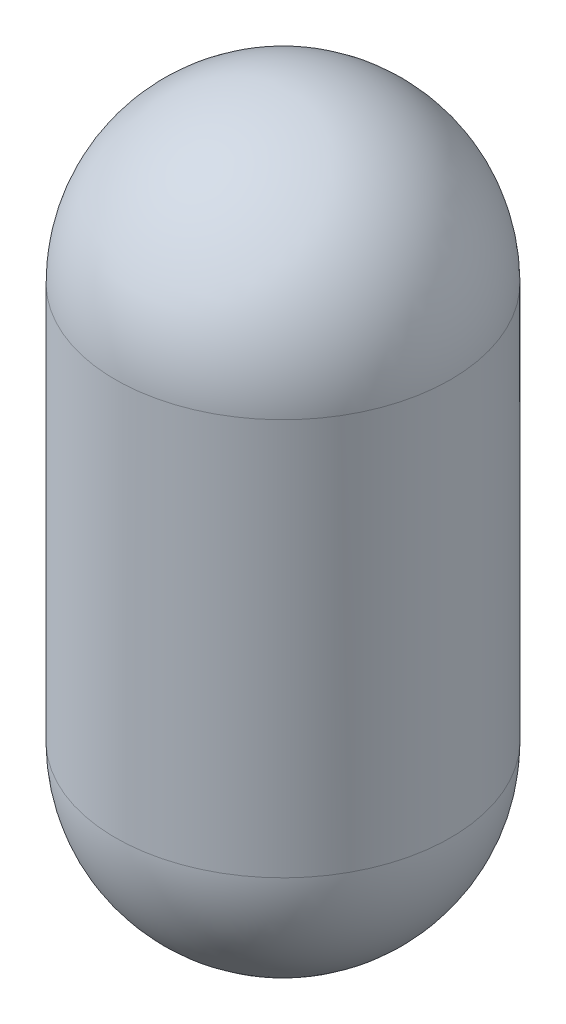
SolidWorks part; units mm, degrees
ref_plane "Front Plane" through (0, 0, 0) normal (0, 0, 1) x (1, 0, 0)
ref_plane "Top Plane" through (0, 0, 0) normal (0, 1, 0) x (1, 0, 0)
ref_plane "Right Plane" through (0, 0, 0) normal (1, 0, 0) x (0, 0, -1)
sketch "Sketch1" plane through (0, 0, 0) normal (0, 0, 1) x (1, 0, 0)
  line L0 (0, 43.9737) -> (0, -43.9737) construction
  line L2 (-37.1475, 43.9738) -> (-37.1475, -43.9738)
  line L3 (-35.56, 43.9738) -> (-35.56, -43.9738)
  line L5 (0, 81.1213) -> (0, 79.5338)
  line L6 (0, -81.1213) -> (0, -79.5338)
  line L7 (-37.1475, -43.9738) -> (0, -43.9737) construction
  line L8 (37.1469, 44.1919) -> (37.1475, -43.9735) construction
  line L9 (35.5594, 44.1871) -> (35.56, -43.9735) construction
  line L10 (-37.1475, 43.9738) -> (0, 43.9737) construction
  line L11 (0, 79.5338) -> (0, 43.9737) construction
  line L12 (0, -79.5338) -> (0, -43.9737) construction
  arc A0 (0, 81.1213) -> (-37.1475, 43.9738) centre (0, 43.9737) ccw
  arc A1 (-37.1475, -43.9738) -> (0, -81.1213) centre (0, -43.9737) ccw
  arc A2 (0, 79.5338) -> (-35.56, 43.9738) centre (0, 43.9737) ccw
  arc A3 (-35.56, -43.9738) -> (0, -79.5338) centre (0, -43.9737) ccw
  arc A4 (-35.56, -43.9738) -> (35.56, -43.9735) centre (0, -43.9737) ccw construction
  arc A5 (-37.1475, -43.9738) -> (37.1475, -43.9735) centre (0, -43.9737) ccw construction
  arc A6 (37.1469, 44.1919) -> (-37.1475, 43.9738) centre (0, 43.9737) ccw construction
  arc A7 (35.5594, 44.1871) -> (-35.56, 43.9738) centre (0, 43.9737) ccw construction
  dimension "D1" = 87.9475
  dimension "D2" = 37.1475
  dimension "D3" = 1.5875
revolve "Revolve3" add sketch "Sketch1" angle 360 about L0
